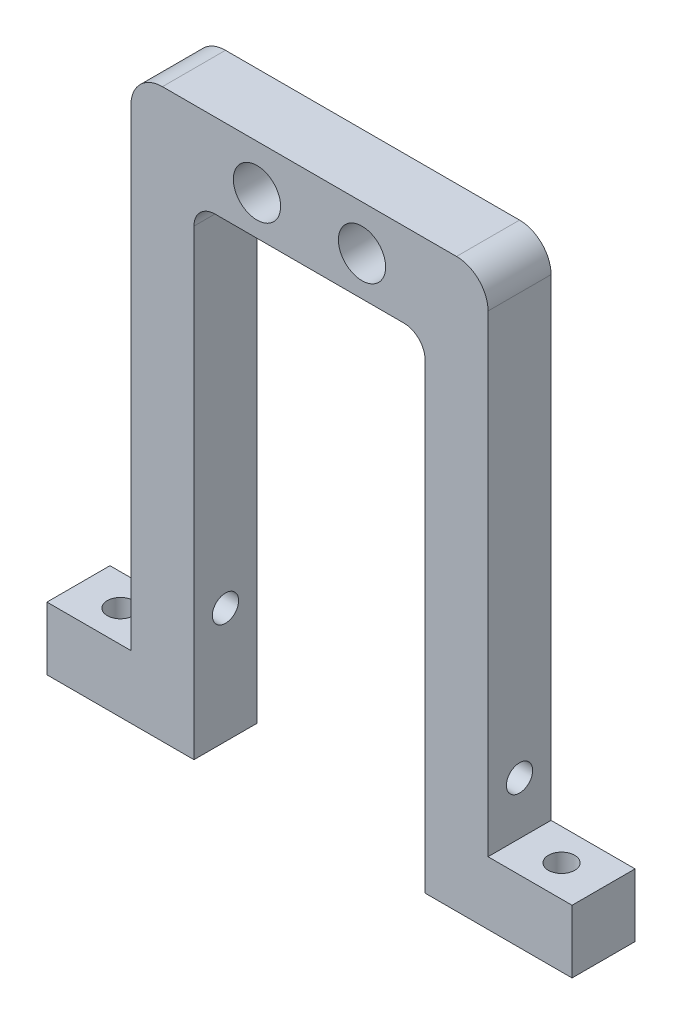
SolidWorks part; units mm, degrees
ref_plane "前视基准面" through (0, 0, 0) normal (0, 0, 1) x (1, 0, 0)
ref_plane "上视基准面" through (0, 0, 0) normal (0, 1, 0) x (1, 0, 0)
ref_plane "右视基准面" through (0, 0, 0) normal (1, 0, 0) x (0, 0, -1)
other "Configuration Table"
sketch "草图1" plane through (0, 0, 0) normal (0, 0, 1) x (1, 0, 0)
  line L0 (0, 0) -> (0, 27) construction
  line L1 (17, -27) -> (-17, -27)
  line L2 (17, -27) -> (17, 27)
  line L3 (17, 27) -> (-17, 27)
  line L4 (-17, -27) -> (-17, 27)
  line L5 (17, -27) -> (-17, 27) construction
  line L6 (17, 27) -> (-17, -27) construction
  line L7 (0, 0) -> (11.0696, 0) construction
  circle A0 centre (-5, 22.75) radius 2.25
  circle A1 centre (5, 22.75) radius 2.25
  point P0 (0, 0)
  dimension "D2" = 4.5
  dimension "D1" = 10
  dimension "D3" = 34
  dimension "D4" = 54
  dimension "D5" = 4.25
extrude "凸台-拉伸1" add sketch "草图1" along normal blind 6
sketch "草图4" plane through (0, 0, 0) normal (0, 0, 1) x (1, 0, 0)
  line L0 (0, 0) -> (0, -27) construction
  line L1 (-17, -27) -> (17, -27) construction
  line L2 (17, -27) -> (25, -27)
  line L3 (25, -27) -> (25, -21)
  line L4 (25, -21) -> (17, -21)
  line L5 (17, -27) -> (17, 27) construction
  line L6 (17, -21) -> (17, -27)
  line L7 (-25, -21) -> (-17, -21)
  line L8 (-25, -27) -> (-25, -21)
  line L9 (-17, -27) -> (-25, -27)
  line L10 (-17, -21) -> (-17, -27)
  dimension "D1" = 8
  dimension "D2" = 6
extrude "凸台-拉伸2" add sketch "草图4" along normal blind 6
sketch "草图2" plane through (0, 0, 6) normal (0, 0, 1) x (1, 0, 0)
  line L5 (0, 0) -> (0, 9.0331) construction
  line L6 (-11, 19) -> (-11, -27)
  line L7 (-25, -27) -> (25, -27) construction
  line L8 (11, 19) -> (11, -27)
  line L9 (-11, 19) -> (11, 19)
  line L10 (11, -27) -> (-11, -27)
  line L11 (17, 27) -> (-17, 27) construction
  dimension "D1" = 22
  dimension "D2" = 8
extrude "切除-拉伸1" cut sketch "草图2" against normal blind 10
fillet "圆角1" radius 3 2 edges at (-17, 27, 3) (17, 27, 3)
fillet "圆角2" radius 2 2 edges at (11, 19, 3) (-11, 19, 3)
hole_wizard "M3 螺纹孔1" positions "草图6" profile "草图7" tap size "M3" standard "GB"
sketch "草图6" plane through (0, -21, 0) normal (0, 1, 0) x (1, 0, 0)
  line L0 (-25, -3) -> (-21, -3) construction
  line L1 (-25, -6) -> (-25, 0) construction
  line L2 (-21, -3) -> (-21, 0) construction
  line L3 (-17, 0) -> (-25, 0) construction
  line L6 (21, 0) -> (21, -3) construction
  line L7 (25, 0) -> (17, 0) construction
  line L8 (21, -3) -> (25, -3) construction
  line L9 (25, -6) -> (25, 0) construction
  point P0 (-21, -3)
  point P2 (21, -3)
cosmetic thread "孔螺蚊线1" parameters "D1"=6, "D2"=3
cosmetic thread "孔螺蚊线2" parameters "D1"=6, "D2"=3
sketch "草图7" plane through (-21, -21, 3) normal (1, 0, 0) x (0, 0, 1)
  line L0 (0, 0) -> (0, 8.2511)
  line L1 (0, 8.2511) -> (1.25, 7.5)
  line L2 (1.25, 7.5) -> (1.25, 0)
  line L5 (1.25, 0) -> (0, 0)
  line L10 (0, 8.2511) -> (-1.25, 7.5) construction
  line L11 (0, -6.35) -> (0, 107.95) construction
  dimension "螺纹孔钻头直径" = 2.5
  dimension "螺纹孔钻头深度" = 7.5
  dimension "导头角度" = 118
hole_wizard "M3 螺纹孔2" positions "草图8" profile "草图9" tap size "M3" standard "GB"
sketch "草图8" plane through (-17, 0, 0) normal (-1, 0, 0) x (0, 0, 1)
  line L0 (3, 24) -> (3, -16) construction
  line L1 (6, 24) -> (0, 24) construction
  point P0 (3, -16)
  dimension "D1" = 40
sketch "草图9" plane through (-17, -16, 3) normal (0, 1, 0) x (0, 0, 1)
  line L0 (0, 0) -> (0, 102.2511)
  line L1 (0, 102.2511) -> (1.25, 101.5)
  line L2 (1.25, 101.5) -> (1.25, 0)
  line L5 (1.25, 0) -> (0, 0)
  line L10 (0, 102.2511) -> (-1.25, 101.5) construction
  line L11 (0, -6.35) -> (0, 107.95) construction
  dimension "螺纹孔钻头直径" = 2.5
  dimension "螺纹孔钻头深度" = 101.5
  dimension "导头角度" = 118
cosmetic thread "孔螺蚊线3" parameters "D1"=100, "D2"=3
